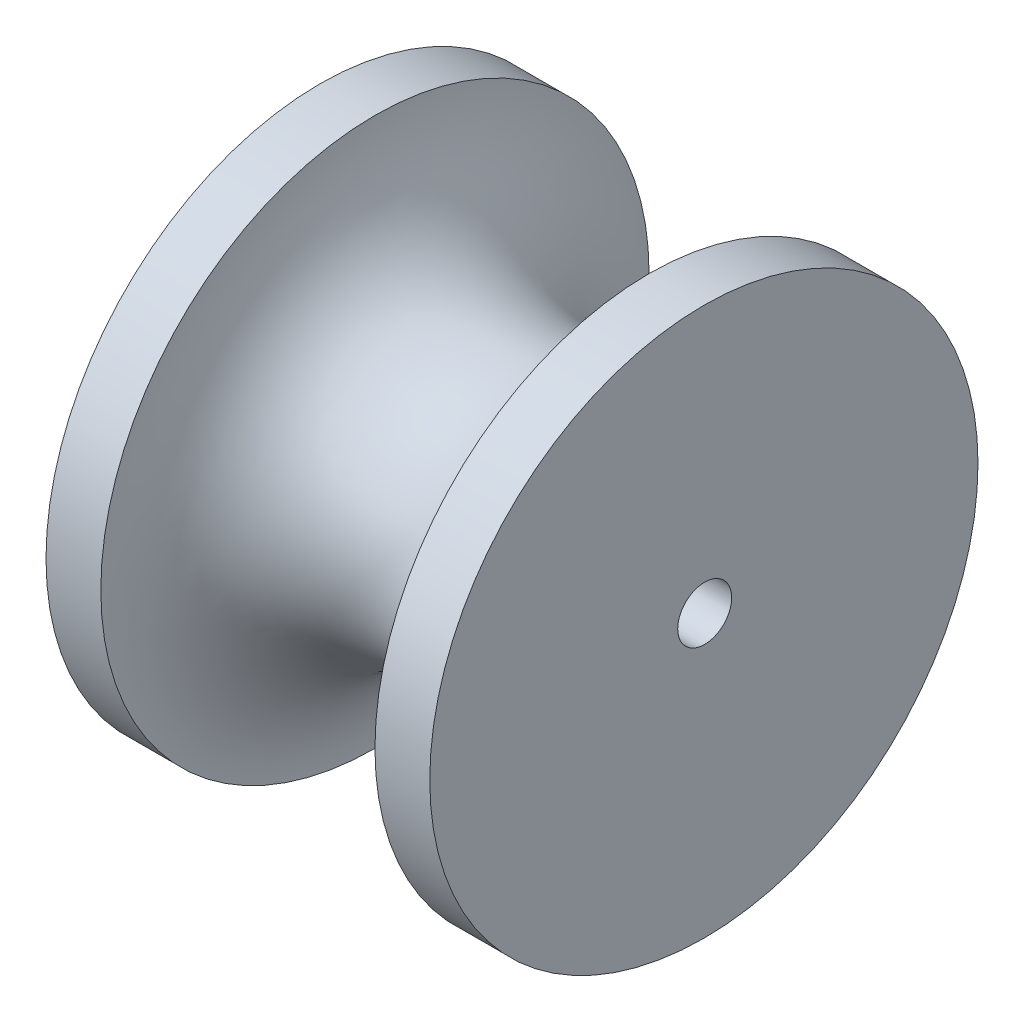
SolidWorks part; units mm, degrees
ref_plane "Front Plane" through (0, 0, 0) normal (0, 0, 1) x (1, 0, 0)
ref_plane "Top Plane" through (0, 0, 0) normal (0, 1, 0) x (1, 0, 0)
ref_plane "Right Plane" through (0, 0, 0) normal (1, 0, 0) x (0, 0, -1)
sketch "Sketch1" plane through (0, 0, 0) normal (0, 0, 1) x (1, 0, 0)
  line L0 (-55.7681, -1.9346) -> (-50.6881, -1.9346)
  line L1 (-25.2881, -1.9346) -> (-20.2081, -1.9346)
  line L2 (-55.7681, -1.9346) -> (-55.7681, -27.3346)
  line L3 (-55.7681, -27.3346) -> (-20.2081, -27.3346)
  line L4 (-20.2081, -27.3346) -> (-20.2081, -1.9346)
  arc A0 (-50.6881, -1.9346) -> (-25.2881, -1.9346) centre (-37.9881, -1.9346) ccw
revolve "Revolve1" add sketch "Sketch1" angle 360 about L3
hole_wizard "#97 (0.0059) Diameter Hole2" positions "Sketch4" profile "Sketch2" hole size "#97" standard "ANSI Inch" end condition through all
sketch "Sketch4" plane through (-55.7681, 0, 0) normal (-1, 0, 0) x (0, 0, 1)
  point P0 (0, -26.6866)
sketch "Sketch2" plane through (-55.7681, -26.6866, 0) normal (0, 1, 0) x (0, 0, 1)
  line L0 (0, 0) -> (0, 35.56)
  line L1 (0, 35.56) -> (0.0749, 35.56)
  line L2 (0.0749, 35.56) -> (0.0749, 0)
  line L5 (0.0749, 0) -> (0, 0)
  line L11 (0, -6.35) -> (0, 107.95) construction
  dimension "Thru Hole Dia." = 0.1499
  dimension "Thru Hole Depth" = 35.56
sketch "Sketch5" plane through (-55.7681, 0, 0) normal (-1, 0, 0) x (0, 0, 1)
  circle A0 centre (-0.0749, -26.6866) radius 2.5
  circle A1 centre (0, -26.6866) radius 0.0749 construction
extrude "Cut-Extrude2" cut sketch "Sketch5" against normal blind 35.56
